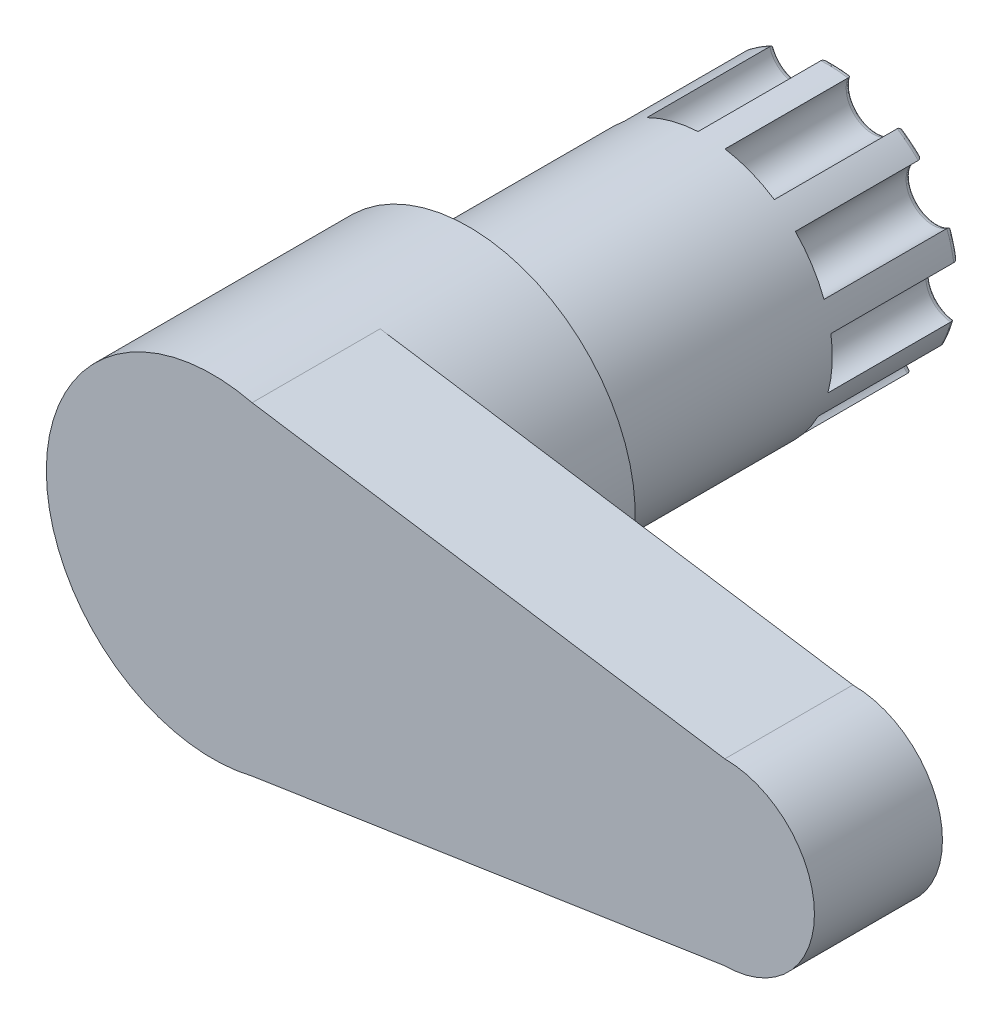
SolidWorks part; units mm, degrees
ref_plane "Спереди" through (0, 0, 0) normal (0, 0, 1) x (1, 0, 0)
ref_plane "Сверху" through (0, 0, 0) normal (0, 1, 0) x (1, 0, 0)
ref_plane "Справа" through (0, 0, 0) normal (1, 0, 0) x (0, 0, -1)
sketch "Эскиз1" plane through (0, 0, 0) normal (0, 0, 1) x (1, 0, 0)
  circle A0 centre (0, 0) radius 2.3 construction
  circle A1 centre (0, 0) radius 5
  dimension "D1" = 10
  dimension "D2" = 4.6
extrude "Бобышка-Вытянуть1" add sketch "Эскиз1" along normal blind 19.2
sketch "Эскиз4" plane through (0, 0, 0) normal (0, 0, -1) x (-1, 0, 0)
  line L1 (0.2459, 4.9939) -> (2.2459, 4.4672) construction
  line L2 (0.9825, 3.7306) -> (1.2734, 4.8351) construction
  circle A0 centre (0, 0) radius 5 construction
  arc A2 (0.2459, 4.9939) -> (2.2459, 4.4672) centre (1.2459, 4.7306) ccw
  arc A4 (0.2459, 4.9939) -> (2.2459, 4.4672) centre (0.6209, 2.3576) cw
  point P5 (0.9825, 3.7306)
  dimension "D1" = 2
  dimension "D2" = 1
extrude "Вырез-Вытянуть3" cut sketch "Эскиз4" against normal blind 5
pattern_circular "Круговой массив3" count 10 over 360 about axis through (0, 0, 0) along (0, 0, 1) of "Вырез-Вытянуть3"
fillet "Скругление7" radius 0.2 20 edges at (-3.8516, 0.2184, 0) (-4.6602, 1.8118, 0) (-4.8351, -1.2734, 0) (-3.2444, -2.0873, 0) (-3.1632, -3.8722, 0) (-1.3979, -3.5956, 0) (-0.283, -4.992, 0) (0.9825, -3.7306, 0) (2.7052, -4.205, 0) (2.9877, -2.4406, 0) (4.6602, -1.8118, 0) (3.8516, -0.2184, 0) (4.8351, 1.2734, 0) (3.2444, 2.0873, 0) (3.1632, 3.8722, 0) (1.3979, 3.5956, 0) (0.283, 4.992, 0) (-0.9825, 3.7306, 0) (-2.7052, 4.205, 0) (-2.9877, 2.4406, 0)
sketch "Эскиз5" plane through (0, 0, 19.2) normal (0, 0, 1) x (1, 0, 0)
  line L0 (1.5379, 6.3155) -> (20, 3.5)
  line L7 (1.5379, -6.3155) -> (20, -3.5)
  circle A2 centre (0, 0) radius 2.3 construction
  arc A3 (1.5379, 6.3155) -> (1.5379, -6.3155) centre (0, 0) ccw
  arc A4 (20, -3.5) -> (20, 3.5) centre (20, 0) ccw
  dimension "D1" = 13
  dimension "D2" = 20
  dimension "D3" = 7
  dimension "D4" = 4.6
extrude "Бобышка-Вытянуть4" add sketch "Эскиз5" along normal blind 5
sketch "Эскиз7" plane through (0, 0, 24.2) normal (0, 0, 1) x (1, 0, 0)
  circle A0 centre (0, 0) radius 4.3
  dimension "D1" = 8.6
extrude "Вырез-Вытянуть4" [suppressed] cut sketch "Эскиз7" against normal blind 3
sketch "Эскиз8" plane through (0, 0, 19.2) normal (0, 0, -1) x (-1, 0, 0)
  circle A0 centre (0, 0) radius 4.9
  circle A1 centre (0, 0) radius 6.5
extrude "Бобышка-Вытянуть5" add sketch "Эскиз8" along normal blind 5
